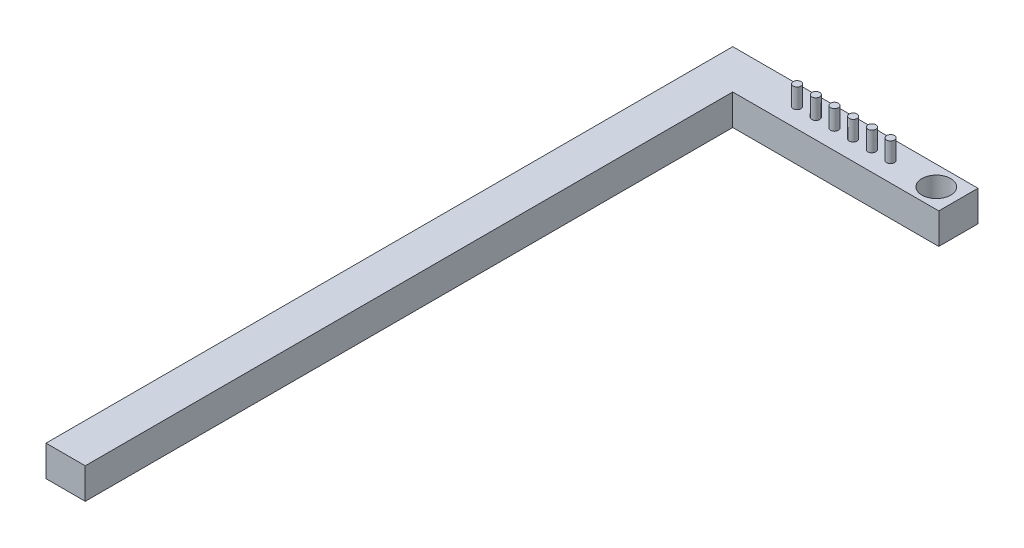
SolidWorks part; units mm, degrees
ref_plane "Front Plane" through (0, 0, 0) normal (0, 0, 1) x (1, 0, 0)
ref_plane "Top Plane" through (0, 0, 0) normal (0, 1, 0) x (1, 0, 0)
ref_plane "Right Plane" through (0, 0, 0) normal (1, 0, 0) x (0, 0, -1)
sketch "Sketch1" plane through (0, 0, 0) normal (0, 1, 0) x (1, 0, 0)
  line L4 (12.5, 2) -> (12.5, -2)
  line L5 (-12.5, 2) -> (12.5, -2) construction
  line L6 (-12.5, -2) -> (12.5, 2) construction
  line L11 (-8.5, 2) -> (12.5, 2)
  line L14 (-8.5, -2) -> (12.5, -2)
  line L18 (-8.5, -2) -> (-8.5, -68)
  line L21 (-8.5, -68) -> (-12.5, -68)
  line L22 (-12.5, 2) -> (-12.5, -68)
  line L24 (-8.5, 2) -> (-12.5, 2)
  circle A1 centre (10.25, 0) radius 1.47
  point P0 (0, 0)
  dimension "D1" = 4
  dimension "D3" = 2.94
  dimension "D2" = 25
  dimension "D4" = 2.25
  dimension "D7" = 70
extrude "Boss-Extrude1" add sketch "Sketch1" along normal blind 3.14
sketch "Sketch6" plane through (0, 3.14, 0) normal (0, 1, 0) x (1, 0, 0)
  circle A0 centre (-3.9359, -0.003) radius 0.4
  circle A1 centre (-2.0309, -0.0026) radius 0.4
  circle A2 centre (-0.1259, -0.0022) radius 0.4
  circle A3 centre (1.7791, -0.0018) radius 0.4
  circle A4 centre (3.6841, -0.0014) radius 0.4
  circle A5 centre (5.5891, -0.001) radius 0.4
  dimension "D1" = 0.8
  dimension "D2" = 0.8
  dimension "D3" = 0.8
  dimension "D4" = 0.8
  dimension "D5" = 0.8
  dimension "D6" = 0.8
extrude "Boss-Extrude4" add sketch "Sketch6" along normal blind 2
ref_plane "Plane1" through (12.5, 3.14, 2) normal (1, 0, 0) x (0, 0, -1)
